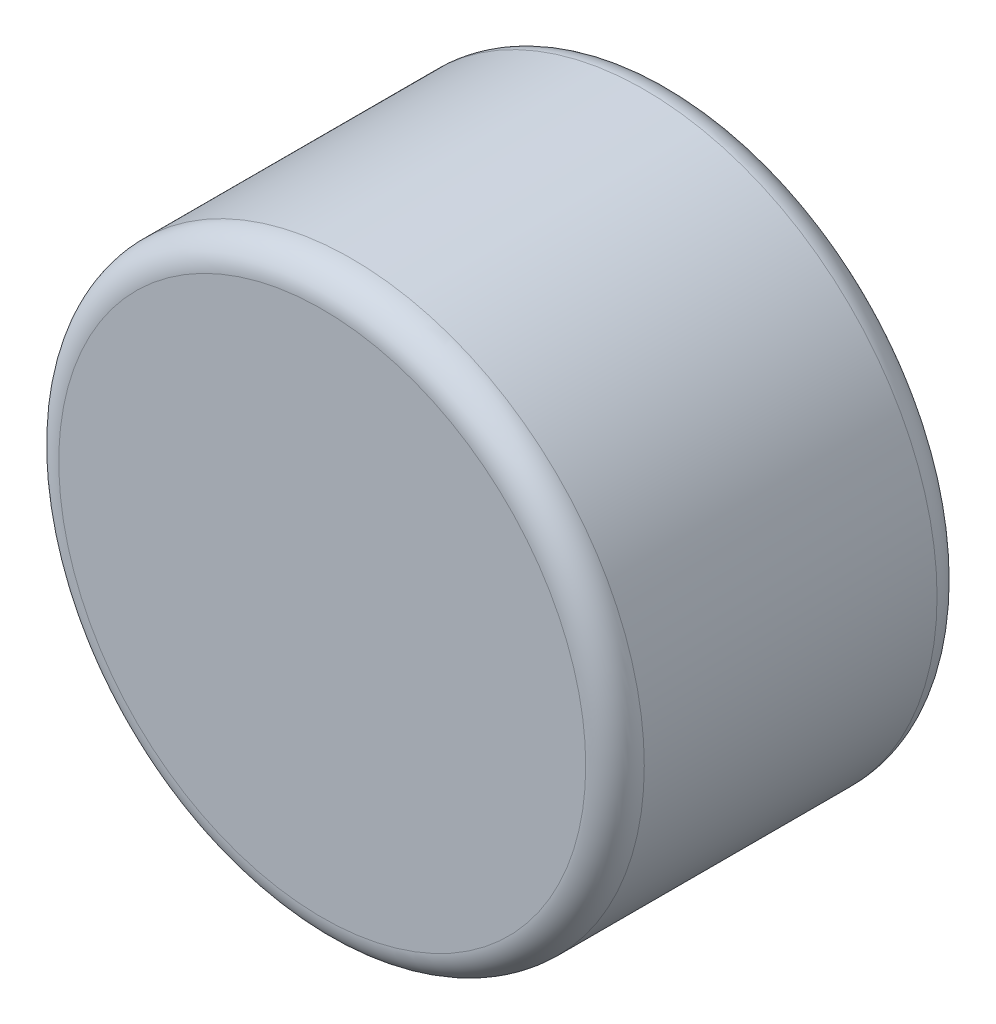
SolidWorks part; units mm, degrees
material "1060-H18 Стержень (SS)"
ref_plane "Спереди" through (0, 0, 0) normal (0, 0, 1) x (1, 0, 0)
ref_plane "Сверху" through (0, 0, 0) normal (0, 1, 0) x (1, 0, 0)
ref_plane "Справа" through (0, 0, 0) normal (1, 0, 0) x (0, 0, -1)
sketch "Эскиз1" plane through (0, 0, 0) normal (0, 0, 1) x (1, 0, 0)
  circle A0 centre (0, 0) radius 2.5
  dimension "D1" = 5
extrude "Бобышка-Вытянуть1" add sketch "Эскиз1" along normal blind 3
fillet "Скругление1" radius 0.25 2 edges at (2.5, 0, 0) (2.5, 0, 3)
